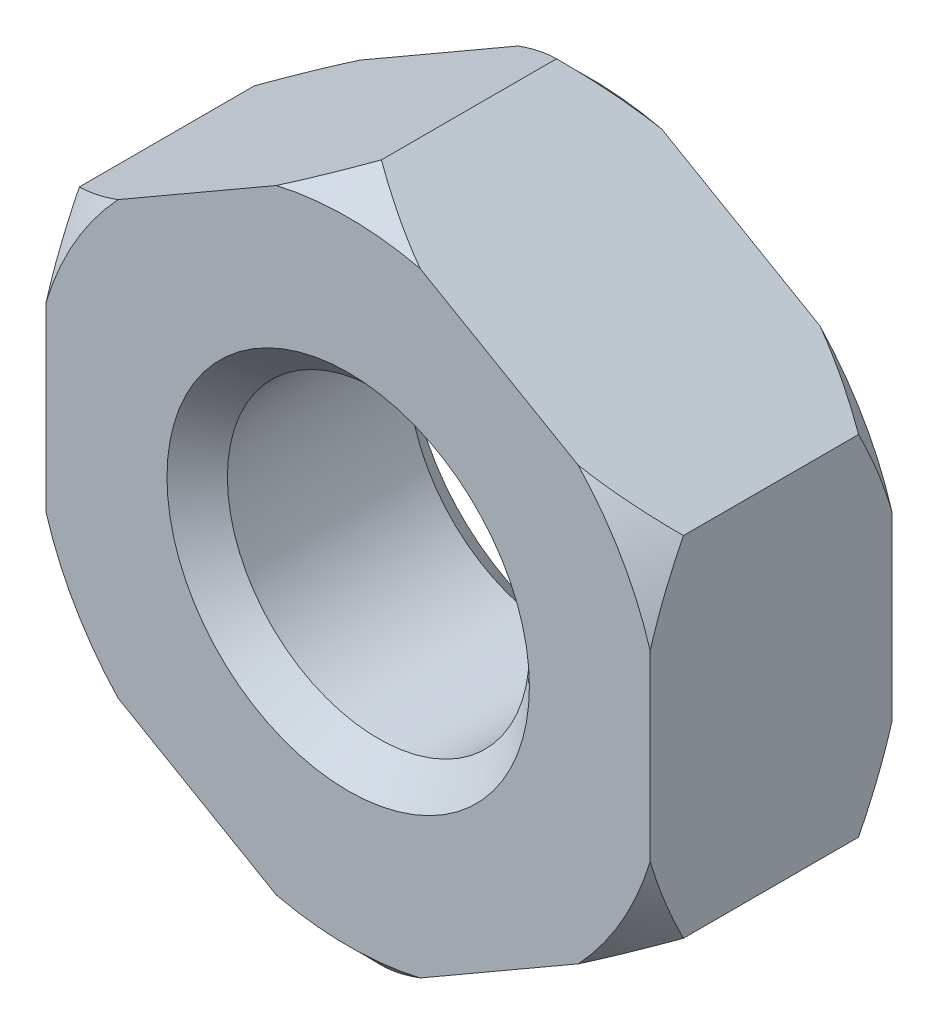
SolidWorks part; units mm, degrees
ref_plane "Спереди" through (0, 0, 0) normal (0, 0, 1) x (1, 0, 0)
ref_plane "Сверху" through (0, 0, 0) normal (0, 1, 0) x (1, 0, 0)
ref_plane "Справа" through (0, 0, 0) normal (1, 0, 0) x (0, 0, -1)
sketch "Эскиз1" plane through (0, 0, 0) normal (0, 0, 1) x (1, 0, 0)
  line L0 (0, 3.7738) -> (0, -4.1898) construction
  line L1 (-3.4469, 0) -> (3.2389, 0) construction
  line L3 (0, 2.8868) -> (-2.5, 1.4434)
  line L4 (-2.5, 1.4434) -> (-2.5, -1.4434)
  line L5 (-2.5, -1.4434) -> (0, -2.8868)
  line L6 (0, -2.8868) -> (2.5, -1.4434)
  line L7 (2.5, -1.4434) -> (2.5, 1.4434)
  line L8 (2.5, 1.4434) -> (0, 2.8868)
  circle A0 centre (0, 0) radius 2.5 construction
extrude "Вытянуть1" add sketch "Эскиз1" along normal blind 2
sketch "Эскиз2" plane through (0, 0, 0) normal (0, 0, -1) x (-1, 0, 0)
  circle A0 centre (0, 0) radius 1.25
ref_axis "Ось4" through (0, 0, 2.6338) along (0, 0, -1)
sketch "Эскиз15" plane through (0, 0, 0) normal (1, 0, 0) x (0, 0, -1)
  line L0 (-2, 2.8868) -> (-2, 2.6118)
  line L1 (-2, 1.4434) -> (-2, 2.8868) construction
  line L2 (-2, 2.6118) -> (-1.725, 2.8868)
  line L3 (-2, 2.8868) -> (0, 2.8868) construction
  line L4 (-1.725, 2.8868) -> (-2, 2.8868)
  line L5 (-0.275, 2.8868) -> (0, 2.8868)
  line L6 (0, 2.8868) -> (0, 2.6118)
  line L7 (0, 2.6118) -> (-0.275, 2.8868)
  line L8 (-2, 2.8868) -> (-2, 1.4434) construction
revolve "Вырез-Повернуть1" cut sketch "Эскиз15" angle 360 about axis through (0, 0, 2.6338) along (0, 0, -1)
ref_plane "Плоскость1" through (2.5, 0.7558, 2) normal (-0.2894, 0.9572, 0) x (-0.9572, -0.2894, 0)
extrude "Вырез-Вытянуть1" cut sketch "Эскиз2" against normal through all
chamfer "Фаска1" distance 0.25 angle 45 2 edges at (-1.25, 0, 0) (-1.25, 0, 2)
